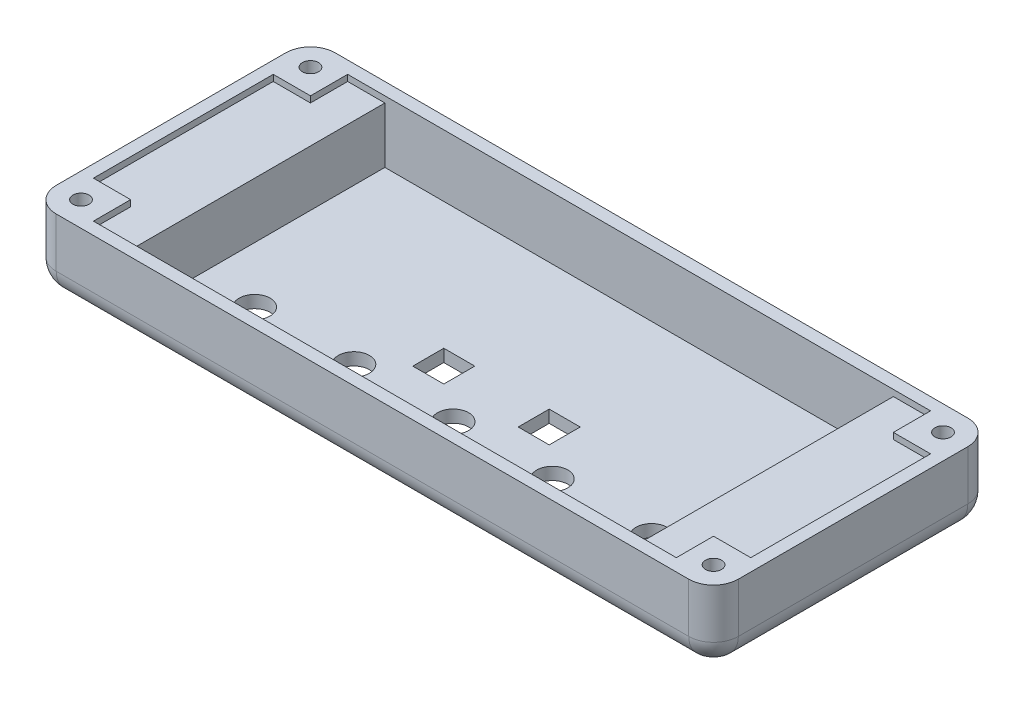
SolidWorks part; units mm, degrees
ref_plane "Front Plane" through (0, 0, 0) normal (0, 0, 1) x (1, 0, 0)
ref_plane "Top Plane" through (0, 0, 0) normal (0, 1, 0) x (1, 0, 0)
ref_plane "Right Plane" through (0, 0, 0) normal (1, 0, 0) x (0, 0, -1)
sketch "Sketch1" plane through (0, 0, 0) normal (0, 1, 0) x (1, 0, 0)
  line L1 (-55, 22.5) -> (55, 22.5)
  line L2 (-55, 22.5) -> (-55, -22.5)
  line L3 (-55, -22.5) -> (55, -22.5)
  line L4 (55, 22.5) -> (55, -22.5)
  line L5 (-55, 22.5) -> (55, -22.5) construction
  line L6 (-55, -22.5) -> (55, 22.5) construction
  point P0 (0, 0)
  dimension "D1" = 45
  dimension "D2" = 110
extrude "Boss-Extrude1" add sketch "Sketch1" along normal blind 2
sketch "Sketch3" plane through (0, 2, 0) normal (0, 1, 0) x (1, 0, 0)
  line L1 (-55, 22.5) -> (55, 22.5)
  line L2 (-55, 22.5) -> (-55, -22.5)
  line L3 (-55, -22.5) -> (55, -22.5)
  line L4 (55, 22.5) -> (55, -22.5)
  line L5 (-55, 22.5) -> (55, -22.5) construction
  line L6 (-55, -22.5) -> (55, 22.5) construction
  line L7 (-53, 20.5) -> (53, 20.5)
  line L8 (-53, 20.5) -> (-53, -20.5)
  line L9 (-53, -20.5) -> (53, -20.5)
  line L10 (53, 20.5) -> (53, -20.5)
  line L11 (-53, 20.5) -> (53, -20.5) construction
  line L12 (-53, -20.5) -> (53, 20.5) construction
  point P0 (0, 0)
  point P7 (0, 0)
  dimension "D1" = 41
  dimension "D2" = 106
extrude "Boss-Extrude2" add sketch "Sketch3" along normal blind 10
sketch "Sketch4" plane through (0, 2, 0) normal (0, 1, 0) x (1, 0, 0)
  line L0 (-53, -20.5) -> (53, -20.5) construction
  line L1 (-53, 20.5) -> (-41, 20.5)
  line L2 (-53, 20.5) -> (-53, -20.5)
  line L3 (-53, -20.5) -> (-41, -20.5)
  line L4 (-41, 20.5) -> (-41, -20.5)
  line L5 (-53, -20.5) -> (53, -20.5) construction
  line L6 (53, 20.5) -> (41, 20.5)
  line L7 (53, 20.5) -> (53, -20.5)
  line L8 (53, -20.5) -> (41, -20.5)
  line L9 (41, 20.5) -> (41, -20.5)
  dimension "D1" = 12
  dimension "D2" = 12
extrude "Boss-Extrude3" add sketch "Sketch4" along normal blind 9
sketch "Sketch5" plane through (0, 11, 0) normal (0, 1, 0) x (1, 0, 0)
  line L1 (-53, 20.5) -> (-47, 20.5)
  line L2 (-53, 20.5) -> (-53, 14.5)
  line L3 (-53, 14.5) -> (-47, 14.5)
  line L4 (-47, 20.5) -> (-47, 14.5)
  line L5 (-53, -20.5) -> (-47, -20.5)
  line L6 (-53, -20.5) -> (-53, -14.5)
  line L7 (-53, -14.5) -> (-47, -14.5)
  line L8 (-47, -20.5) -> (-47, -14.5)
  dimension "D1" = 6
  dimension "D2" = 6
  dimension "D3" = 6
  dimension "D4" = 6
extrude "Boss-Extrude4" add sketch "Sketch5" along normal blind 1
sketch "Sketch6" plane through (0, 11, 0) normal (0, 1, 0) x (1, 0, 0)
  line L1 (53, 20.5) -> (47, 20.5)
  line L2 (53, 20.5) -> (53, 14.5)
  line L3 (53, 14.5) -> (47, 14.5)
  line L4 (47, 20.5) -> (47, 14.5)
  line L5 (53, -20.5) -> (47, -20.5)
  line L6 (53, -20.5) -> (53, -14.5)
  line L7 (53, -14.5) -> (47, -14.5)
  line L8 (47, -20.5) -> (47, -14.5)
  dimension "D1" = 6
  dimension "D2" = 6
  dimension "D3" = 6
  dimension "D4" = 6
extrude "Boss-Extrude5" add sketch "Sketch6" along normal blind 1
fillet "Fillet1" radius 4 4 edges at (55, 6, -22.5) (55, 6, 22.5) (-55, 6, 22.5) (-55, 6, -22.5)
fillet "Fillet2" radius 4 8 edges at (53.8284, 0, 21.3284) (53.8284, 0, -21.3284) (55, 0, 0) (-53.8284, 0, 21.3284) (0, 0, 22.5) (-53.8284, 0, -21.3284) (-55, 0, 0) (0, 0, -22.5)
sketch "Sketch7" plane through (0, 12, 0) normal (0, 1, 0) x (1, 0, 0)
  circle A0 centre (-51, 18.5) radius 1.3
  circle A1 centre (51, 18.5) radius 1.3
  circle A2 centre (51, -18.5) radius 1.3
  circle A3 centre (-51, -18.5) radius 1.3
  dimension "D1" = 2.6
  dimension "D2" = 2.6
  dimension "D3" = 2.6
  dimension "D4" = 2.6
extrude "Cut-Extrude1" cut sketch "Sketch7" against normal blind 8
sketch "Sketch9" plane through (0, 0, 0) normal (0, -1, 0) x (1, 0, 0)
  line L0 (-51, 18.5) -> (-51, -18.5) construction
  line L2 (-51, -18.5) -> (51, -18.5) construction
  line L3 (51, -18.5) -> (51, 18.5) construction
  line L4 (-11, 5) -> (-6, 5)
  line L5 (-11, 5) -> (-11, 0)
  line L6 (-11, 0) -> (-6, 0)
  line L7 (-6, 5) -> (-6, 0)
  line L8 (-11, 5) -> (-6, 0) construction
  line L9 (-11, 0) -> (-6, 5) construction
  line L10 (6, 5) -> (11, 5)
  line L11 (6, 5) -> (6, 0)
  line L12 (6, 0) -> (11, 0)
  line L13 (11, 5) -> (11, 0)
  line L14 (6, 5) -> (11, 0) construction
  line L15 (6, 0) -> (11, 5) construction
  circle A0 centre (-32, 9.5) radius 2.5
  circle A1 centre (-16, 9.5) radius 2.5
  circle A2 centre (0, 9.5) radius 2.5
  circle A3 centre (16, 9.5) radius 2.5
  circle A4 centre (32, 9.5) radius 2.5
  point P16 (-8.5, 2.5)
  point P21 (8.5, 2.5)
  dimension "D1" = 5
  dimension "D2" = 19
  dimension "D3" = 5
  dimension "D4" = 5
  dimension "D5" = 5
  dimension "D6" = 5
  dimension "D9" = 16
  dimension "D10" = 16
  dimension "D12" = 28
  dimension "D13" = 28
  dimension "D14" = 28
  dimension "D15" = 28
  dimension "D16" = 19
  dimension "D11" = 28
  dimension "D21" = 7
  dimension "D24" = 7.5
  dimension "D7" = 16
  dimension "D8" = 16
  dimension "D17" = 5
  dimension "D18" = 5
  dimension "D19" = 5
  dimension "D20" = 5
  dimension "D22" = 0
  dimension "D23" = 12
extrude "Cut-Extrude3" cut sketch "Sketch9" against normal blind 5
sketch "Sketch10" plane through (0, 0, 0) normal (0, -1, 0) x (1, 0, 0)
  line L0 (-51, -18.5) -> (51, -18.5) construction
  line L1 (-51, 18.5) -> (-51, -18.5) construction
  text T0 "STATUS" font "Century Gothic" height 2
  text T1 "PREHEAT" font "Century Gothic" height 2
  text T2 "SOAK" font "Century Gothic" height 2
  text T3 "REFLOW" font "Century Gothic" height 2
  text T4 "COOL" font "Century Gothic" height 2
  dimension "D1" = 32
  dimension "D2" = 29.469
  dimension "D3" = 32
  dimension "D4" = 32
  dimension "D5" = 47.5
  dimension "D6" = 62
  dimension "D7" = 32
  dimension "D8" = 32
  dimension "D9" = 79
extrude "Cut-Extrude4" cut sketch "Sketch10" against normal blind 1
